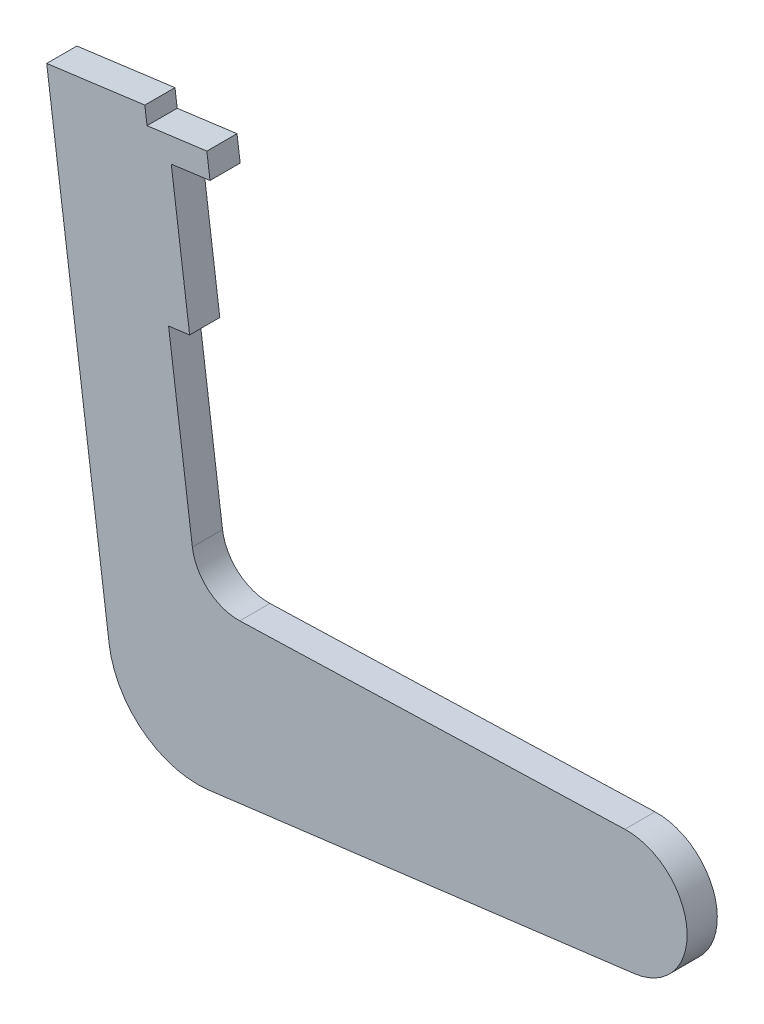
SolidWorks part; units mm, degrees
material "Plain Carbon Steel"
ref_plane "Front Plane" through (0, 0, 0) normal (0, 0, 1) x (1, 0, 0)
ref_plane "Top Plane" through (0, 0, 0) normal (0, 1, 0) x (1, 0, 0)
ref_plane "Right Plane" through (0, 0, 0) normal (1, 0, 0) x (0, 0, -1)
sketch "Sketch1" plane through (0, 0, 0) normal (0, 0, 1) x (1, 0, 0)
  point P0 (0, 0)
  line B0 (-11.4373, 39.0502) -> (-4.7473, 45.8293)
  line B1 (-4.7473, 45.8293) -> (-4.9808, 47.592)
  line B2 (-4.9808, 47.592) -> (-15.3046, 46.2245)
  line B3 (-15.3046, 46.2245) -> (-8.7339, -3.3803)
  line B4 (1.7621, -11.47) -> (46.5302, -5.8079)
  line B5 (45.5334, 6.8529) -> (5.0154, 5.583)
  line B6 (0.0223, 9.8219) -> (-2.4793, 28.7069)
  line B7 (-4.7473, 45.8293) -> (-2.4793, 28.7069)
  line B8 (-2.4793, 28.7069) -> (-0.2634, 29.0004)
  line B9 (-0.2634, 29.0004) -> (-2.1979, 43.6049)
  line B10 (-2.1979, 43.6049) -> (1.8812, 44.1452)
  line B11 (1.8812, 44.1452) -> (1.5477, 46.6632)
  line B12 (1.5477, 46.6632) -> (-4.7473, 45.8293)
  circle B13 centre (0, 0) radius 6.35
  arc B14 (-8.7339, -3.3803) -> (1.7621, -11.47) centre (0.5828, -2.1462) ccw
  arc B15 (46.5302, -5.8079) -> (45.5334, 6.8529) centre (45.7325, 0.499) ccw
  arc B16 (0.0223, 9.8219) -> (5.0154, 5.583) centre (4.8624, 10.463) ccw
sketch_block_instance "Cam Geometry-1"
sketch_block "Cam Geometry"
sketch "Sketch2" plane through (0, 0, 0) normal (0, 0, 1) x (1, 0, 0)
  line L0 (-4.9808, 47.592) -> (-15.3046, 46.2245) construction
  line L1 (0.0223, 9.8219) -> (-2.4793, 28.7069) construction
  line L2 (-2.4793, 28.7069) -> (-0.2634, 29.0004) construction
  line L3 (-4.7473, 45.8293) -> (-4.9808, 47.592) construction
  line L4 (-0.2634, 29.0004) -> (-2.1979, 43.6049) construction
  line L5 (-2.1979, 43.6049) -> (1.8812, 44.1452) construction
  line L6 (1.8812, 44.1452) -> (1.5477, 46.6632) construction
  line L7 (1.5477, 46.6632) -> (-4.7473, 45.8293) construction
  line L8 (-15.3046, 46.2245) -> (-8.7339, -3.3803) construction
  line L9 (0.0223, 9.8219) -> (-2.4793, 28.7069)
  line L10 (-2.4793, 28.7069) -> (-0.2634, 29.0004)
  line L11 (-4.7473, 45.8293) -> (-4.9808, 47.592)
  line L12 (-0.2634, 29.0004) -> (-2.1979, 43.6049)
  line L13 (-2.1979, 43.6049) -> (1.8812, 44.1452)
  line L14 (1.8812, 44.1452) -> (1.5477, 46.6632)
  line L15 (1.5477, 46.6632) -> (-4.7473, 45.8293)
  line L16 (-4.9808, 47.592) -> (-15.3046, 46.2245)
  line L17 (-15.3046, 46.2245) -> (-8.7339, -3.3803)
  line L18 (1.7621, -11.47) -> (46.5302, -5.8079) construction
  line L19 (45.5334, 6.8529) -> (5.0154, 5.583) construction
  line L20 (1.7621, -11.47) -> (46.5302, -5.8079)
  line L21 (45.5334, 6.8529) -> (5.0154, 5.583)
  circle A0 centre (0, 0) radius 6.35 construction
  arc A1 (-8.7339, -3.3803) -> (1.7621, -11.47) centre (0.5828, -2.1462) ccw construction
  arc A2 (46.5302, -5.8079) -> (45.5334, 6.8529) centre (45.7325, 0.499) ccw construction
  arc A3 (0.0223, 9.8219) -> (5.0154, 5.583) centre (4.8624, 10.463) ccw construction
  circle A4 centre (0, 0) radius 6.35 construction
  arc A5 (-8.7339, -3.3803) -> (1.7621, -11.47) centre (0.5828, -2.1462) ccw
  arc A6 (46.5302, -5.8079) -> (45.5334, 6.8529) centre (45.7325, 0.499) ccw
  arc A7 (0.0223, 9.8219) -> (5.0154, 5.583) centre (4.8624, 10.463) ccw
extrude "Boss-Extrude1" add sketch "Sketch2" along normal mid plane 3.175
